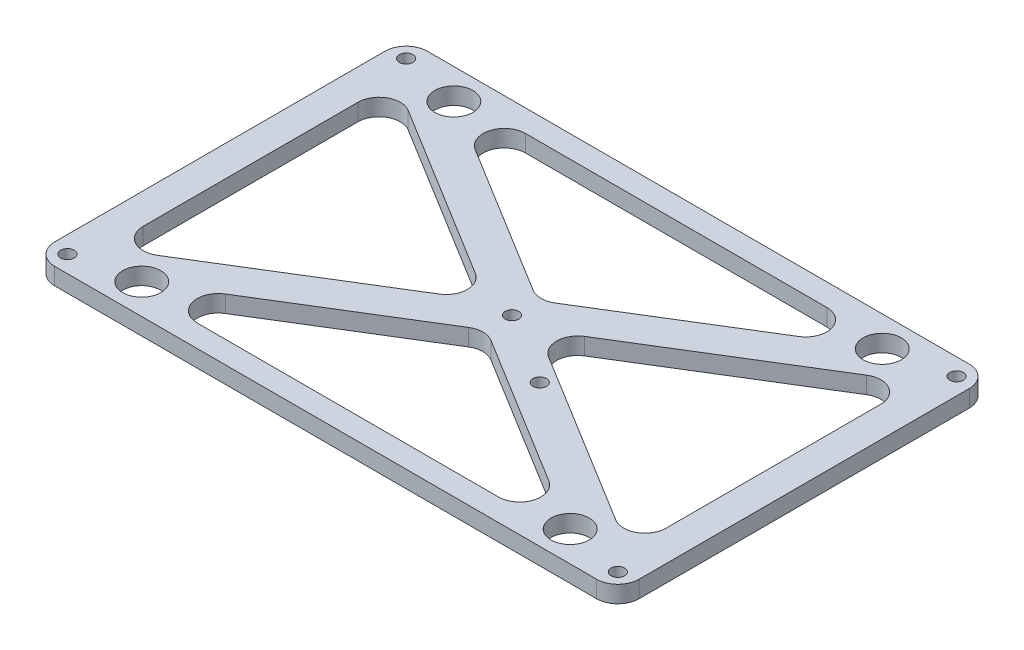
SolidWorks part; units mm, degrees
material "Hexcel AS4C (3000 丝)"
ref_plane "前视基准面" through (0, 0, 0) normal (0, 0, 1) x (1, 0, 0)
ref_plane "上视基准面" through (0, 0, 0) normal (0, 1, 0) x (1, 0, 0)
ref_plane "右视基准面" through (0, 0, 0) normal (1, 0, 0) x (0, 0, -1)
sketch "草图1" plane through (0, 0, 0) normal (0, 1, 0) x (1, 0, 0)
  line L0 (0, 0) -> (0, 44) construction
  line L1 (-65, -40) -> (65, -40) construction
  line L2 (-65, -40) -> (-65, 40) construction
  line L3 (-65, 40) -> (65, 40) construction
  line L4 (65, -40) -> (65, 40) construction
  line L5 (-65, -40) -> (65, 40) construction
  line L6 (-65, 40) -> (65, -40) construction
  line L7 (-69, 44) -> (69, 44)
  line L8 (-69, 44) -> (-69, -44)
  line L9 (-69, -44) -> (69, -44)
  line L10 (69, 44) -> (69, -44)
  line L11 (-69, 44) -> (69, -44) construction
  line L12 (-69, -44) -> (69, 44) construction
  line L13 (-53.25, 38.7692) -> (0, 6)
  line L14 (0, 0) -> (-69, 0) construction
  line L15 (53.25, 38.7692) -> (0, 6)
  line L16 (53.25, -38.7692) -> (0, -6)
  line L17 (-53.25, -38.7692) -> (0, -6)
  line L18 (-53.25, 38.7692) -> (53.25, 38.7692)
  line L19 (-61.75, -34.3077) -> (-6, 0)
  line L20 (61.75, -34.3077) -> (6, 0)
  line L22 (-61.75, 34.3077) -> (-61.75, -34.3077)
  line L23 (-53.25, -38.7692) -> (53.25, -38.7692)
  line L24 (-61.75, 34.3077) -> (-6, 0)
  line L25 (61.75, 34.3077) -> (61.75, -34.3077)
  line L26 (61.75, 34.3077) -> (6, 0)
  circle A0 centre (65, 40) radius 1.6
  circle A1 centre (65, -40) radius 1.6
  circle A2 centre (-65, -40) radius 1.6
  circle A3 centre (-65, 40) radius 1.6
  point P0 (0, 0)
  point P10 (0, 0)
  dimension "D1" = 3.2
  dimension "D2" = 80
  dimension "D3" = 130
  dimension "D4" = 88
  dimension "D5" = 138
  dimension "D6" = 6
  dimension "D7" = 6
  dimension "D8" = 53.25
  dimension "D9" = 61.75
  dimension "D10" = 34.3077
extrude "凸台-拉伸1" add sketch "草图1" along normal blind 4
fillet "圆角1" radius 5 12 edges at (61.75, 2, 34.3077) (61.75, 2, -34.3077) (6, 2, 0) (-61.75, 2, 34.3077) (-6, 2, 0) (-61.75, 2, -34.3077) (53.25, 2, 38.7692) (-53.25, 2, 38.7692) (-53.25, 2, -38.7692) (0, 2, -6) (53.25, 2, -38.7692) (0, 2, 6)
fillet "圆角2" radius 5 4 edges at (-69, 2, -44) (69, 2, -44) (69, 2, 44) (-69, 2, 44)
sketch "草图2" plane through (0, 4, 0) normal (0, 1, 0) x (1, 0, 0)
  line L0 (0, 0) -> (61.75, 0) construction
  line L1 (61.75, -25.3599) -> (61.75, 25.3599) construction
  line L2 (0, 0) -> (0, -38.7692) construction
  line L3 (-35.5848, -38.7692) -> (35.5848, -38.7692) construction
  circle A0 centre (50.5868, -36.8559) radius 4.5
  circle A1 centre (-50.5868, -36.8559) radius 4.5
  circle A2 centre (-50.5868, 36.8559) radius 4.5
  circle A3 centre (50.5868, 36.8559) radius 4.5
  dimension "D1" = 9
extrude "切除-拉伸1" cut sketch "草图2" against normal through all
sketch "草图3" plane through (0, 4, 0) normal (0, 1, 0) x (1, 0, 0)
  line L0 (17.0332, -10.4819) -> (0, 0) construction
  line L1 (-65, 40) -> (0, 0) construction
  line L2 (0, 0) -> (-21.0254, 0) construction
  circle A0 centre (17.0332, -10.4819) radius 1.6
  circle A1 centre (0, 0) radius 1.6
  dimension "D1" = 3.2
  dimension "D2" = 20
extrude "切除-拉伸2" cut sketch "草图3" against normal through all
